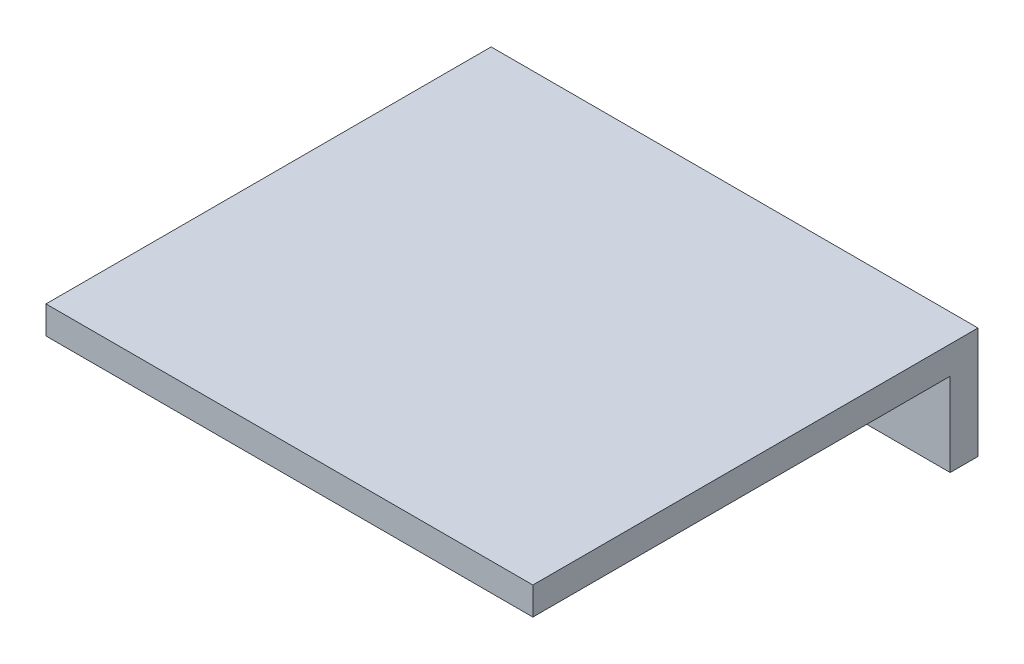
SolidWorks part; units mm, degrees
ref_plane "Front Plane" through (0, 0, 0) normal (0, 0, 1) x (1, 0, 0)
ref_plane "Top Plane" through (0, 0, 0) normal (0, 1, 0) x (1, 0, 0)
ref_plane "Right Plane" through (0, 0, 0) normal (1, 0, 0) x (0, 0, -1)
sketch "Sketch1" plane through (0, 0, 0) normal (0, 0, 1) x (1, 0, 0)
  line L0 (-17.5, 0) -> (17.5, 0) construction
  line L1 (-17.5, 4) -> (17.5, 4)
  line L2 (-17.5, 4) -> (-17.5, -4)
  line L3 (-17.5, -4) -> (17.5, -4)
  line L4 (17.5, 4) -> (17.5, -4)
  line L5 (-17.5, 4) -> (17.5, -4) construction
  line L6 (-17.5, -4) -> (17.5, 4) construction
  line L7 (0, 4) -> (0, -4) construction
  circle A0 centre (12, 0) radius 1.35
  circle A1 centre (-12, 0) radius 1.35
  point P0 (0, 0)
  dimension "D3" = 2.7
  dimension "D1" = 8
  dimension "D2" = 35
  dimension "D4" = 12
extrude "Boss-Extrude1" add sketch "Sketch1" along normal blind 2
sketch "Sketch2" plane through (0, 0, 2) normal (0, 0, 1) x (1, 0, 0)
  line L5 (17.5, 4) -> (-17.5, 4) construction
  line L6 (-17.5, 4) -> (17.5, 4)
  line L7 (-17.5, 4) -> (-17.5, 2)
  line L8 (-17.5, 2) -> (17.5, 2)
  line L9 (17.5, 4) -> (17.5, 2)
  point P0 (0, 0)
  point P8 (0, 2)
  dimension "D1" = 2
  dimension "D2" = 35
extrude "Boss-Extrude3" add sketch "Sketch2" along normal blind 30
sketch "Sketch4" plane through (0, 2, 0) normal (0, -1, 0) x (1, 0, 0)
  line L0 (-17.5, 2) -> (17.5, 2) construction
  line L1 (-15.24, 29.9) -> (15.24, 29.9)
  line L2 (-15.24, 29.9) -> (-15.24, 4.5)
  line L3 (-15.24, 4.5) -> (15.24, 4.5)
  line L4 (15.24, 29.9) -> (15.24, 4.5)
  line L5 (0, 29.9) -> (0, 4.5) construction
  line L7 (-12.7236, 27.4484) -> (12.7236, 27.4484)
  line L8 (-12.7236, 27.4484) -> (-12.7236, 22.4484)
  line L9 (-12.7236, 22.4484) -> (12.7236, 22.4484)
  line L10 (12.7236, 27.4484) -> (12.7236, 22.4484)
  line L11 (-15.24, 9.5) -> (15.24, 9.5)
  line L12 (-15.24, 9.5) -> (-15.24, 4.5)
  line L13 (-15.24, 4.5) -> (15.24, 4.5)
  line L14 (15.24, 9.5) -> (15.24, 4.5)
  circle A0 centre (-12.7236, 27.4484) radius 1.6
  circle A1 centre (12.7236, 27.4484) radius 1.6
  point P4 (0, 4.5)
  point P14 (0, 22.4484)
  dimension "D6" = 3.2
  dimension "D1" = 25.4
  dimension "D2" = 30.48
  dimension "D3" = 2.5
  dimension "D4" = 5
  dimension "D5" = 5
